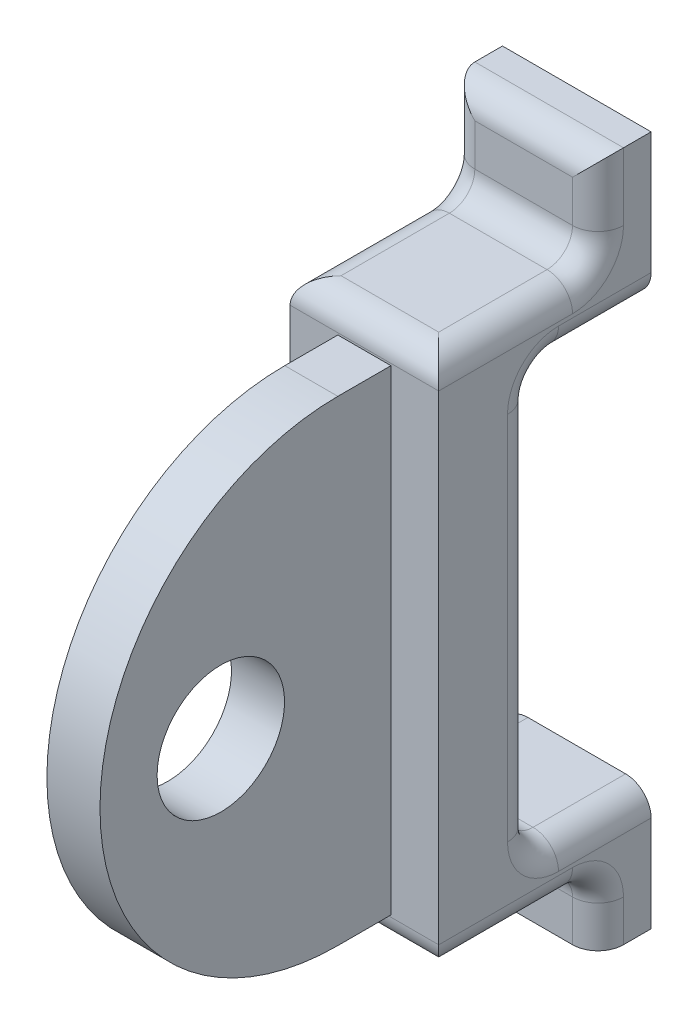
SolidWorks part; units mm, degrees
material "6061-T6 (SS)"
ref_plane "Front Plane" through (0, 0, 0) normal (1, 0, 0) x (0, 1, 0)
ref_plane "Top Plane" through (0, 0, 0) normal (0, 0, 1) x (0, 1, 0)
ref_plane "Right Plane" through (0, 0, 0) normal (0, 1, 0) x (-1, 0, 0)
sketch "Sketch3" plane through (0, 0, 0) normal (1, 0, 0) x (0, 1, 0)
  line L16 (-19.8628, 0) -> (-19.8628, 3.175)
  line L17 (-19.8628, 3.175) -> (-15.8648, 3.175)
  line L18 (-15.8648, 3.175) -> (-15.8648, 12.7)
  line L19 (-15.8648, 12.7) -> (15.8648, 12.7)
  line L20 (15.8648, 12.7) -> (15.8648, 3.175)
  line L21 (15.8648, 3.175) -> (21.4122, 3.175)
  line L22 (21.4122, 3.175) -> (21.4122, 0)
  line L24 (-19.8628, 0) -> (-12.5984, 0)
  line L25 (-12.5984, 0) -> (-12.5984, 7.0612)
  line L26 (-12.5984, 7.0612) -> (12.5984, 7.0612)
  line L27 (12.5984, 7.0612) -> (12.5984, 0)
  line L28 (12.5984, 0) -> (21.4122, 0)
  point P2 (0, 7.0612)
  point P14 (0, 12.7)
  dimension "D1" = 12.7
  dimension "D2" = 12.7
  dimension "D3" = 3.175
  dimension "D4" = 3.175
  dimension "D5" = 41.275
  dimension "D6" = 25.1968
  dimension "D7" = 31.7297
  dimension "D8" = 5.6388
extrude "Boss-Extrude1" add sketch "Sketch3" against normal mid plane 8.89
sketch "Sketch4" plane through (0, 0, 0) normal (1, 0, 0) x (0, 1, 0)
  line L0 (-14.224, 12.7) -> (-14.224, 15.875)
  line L1 (15.8648, 12.7) -> (-15.8648, 12.7) construction
  line L2 (14.224, 15.875) -> (14.224, 12.7)
  line L3 (15.8648, 12.7) -> (14.224, 12.7)
  line L15 (-19.8628, 0) -> (-12.5984, 0)
  line L16 (-12.5984, 0) -> (-12.5984, 7.0612)
  line L17 (-12.5984, 7.0612) -> (12.5984, 7.0612)
  line L18 (12.5984, 7.0612) -> (12.5984, 0)
  line L19 (12.5984, 0) -> (21.4122, 0)
  line L20 (21.4122, 0) -> (21.4122, 3.175)
  line L21 (21.4122, 3.175) -> (15.8648, 3.175)
  line L22 (15.8648, 3.175) -> (15.8648, 12.7)
  line L23 (15.8648, 12.7) -> (-15.8648, 12.7)
  line L24 (-15.8648, 12.7) -> (-15.8648, 3.175)
  line L25 (-15.8648, 3.175) -> (-19.8628, 3.175)
  line L26 (-19.8628, 3.175) -> (-19.8628, 0)
  line L27 (-19.8628, 0) -> (-12.5984, 0)
  line L28 (-12.5984, 0) -> (-12.5984, 7.0612)
  line L29 (-12.5984, 7.0612) -> (12.5984, 7.0612)
  line L30 (12.5984, 7.0612) -> (12.5984, 0)
  line L31 (12.5984, 0) -> (21.4122, 0)
  line L32 (21.4122, 0) -> (21.4122, 3.175)
  line L33 (21.4122, 3.175) -> (15.8648, 3.175)
  line L34 (15.8648, 3.175) -> (15.8648, 12.7)
  line L35 (-14.224, 12.7) -> (-15.8648, 12.7)
  line L36 (-15.8648, 12.7) -> (-15.8648, 3.175)
  line L37 (-15.8648, 3.175) -> (-19.8628, 3.175)
  line L38 (-19.8628, 3.175) -> (-19.8628, 0)
  arc A0 (-14.224, 15.875) -> (14.224, 15.875) centre (0, 15.875) cw
  point P6 (0, 30.099)
  dimension "D2" = 14.224
  dimension "D1" = 3.175
  dimension "D3" = 0
extrude "Boss-Extrude2" add sketch "Sketch4" along normal mid plane 3.175
sketch "Sketch5" plane through (4.445, 0, 0) normal (1, 0, 0) x (0, 1, 0)
  circle A0 centre (0, 22.8736) radius 3.81
  arc A1 (14.224, 15.875) -> (-14.224, 15.875) centre (0, 15.875) ccw construction
  dimension "D1" = 7.62
  dimension "D2" = 6.9986
extrude "Cut-Extrude1" cut sketch "Sketch5" against normal blind 127
fillet "Fillet2" radius 1.524 7 edges at (-4.445, 18.6385, 3.175) (0, 21.4122, 3.175) (4.445, 18.6385, 3.175) (0, 15.8648, 12.7) (-4.445, 15.8648, 7.9375) (0, 15.8648, 3.175) (4.445, 15.8648, 7.9375)
fillet "Fillet3" radius 1.524 6 edges at (-4.445, -17.8638, 3.175) (4.445, -17.8638, 3.175) (0, -15.8648, 3.175) (-4.445, -15.8648, 7.9375) (0, -15.8648, 12.7) (4.445, -15.8648, 7.9375)
fillet "Fillet4" radius 1.524 8 edges at (-4.445, -12.5984, 3.5306) (-4.445, 12.5984, 3.5306) (4.445, -12.5984, 3.5306) (4.445, 12.5984, 3.5306) (-4.445, 0, 7.0612) (0, -12.5984, 7.0612) (4.445, 0, 7.0612) (0, 12.5984, 7.0612)
equation "\"A\"= 1.125in"
equation "\"B\"= 0.125"
equation "\"C\"= 0.5in"
equation "\"D\"= 0.125"
equation "\"E\"= 0.375"
